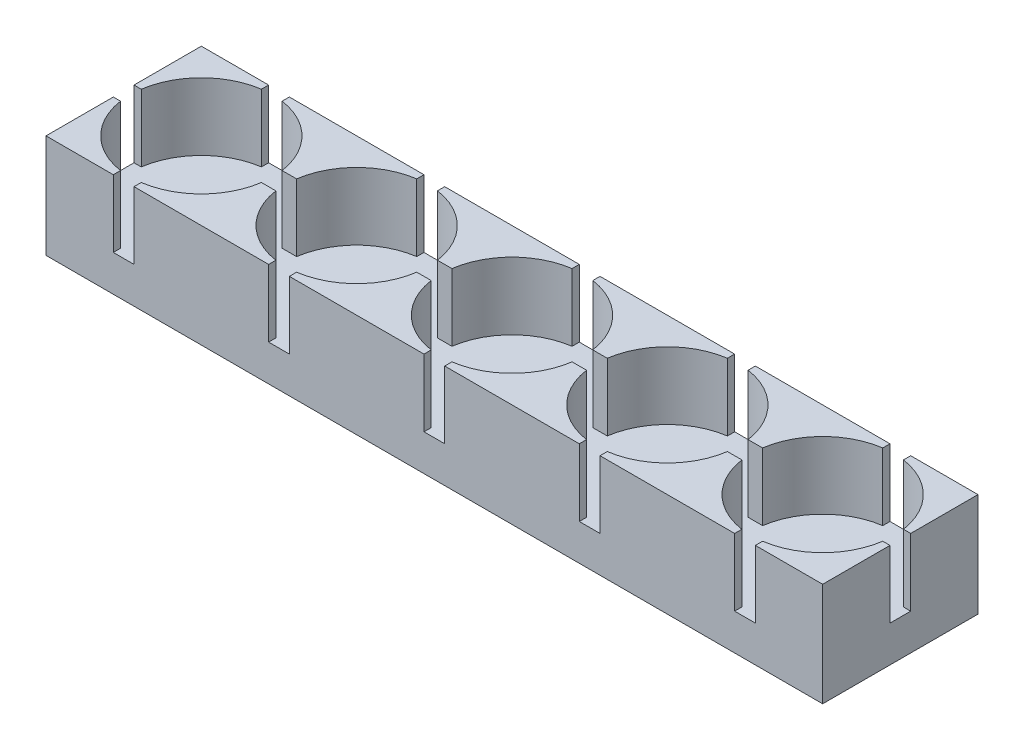
SolidWorks part; units mm, degrees
ref_plane "Front Plane" through (0, 0, 0) normal (0, 0, 1) x (1, 0, 0)
ref_plane "Top Plane" through (0, 0, 0) normal (0, 1, 0) x (1, 0, 0)
ref_plane "Right Plane" through (0, 0, 0) normal (1, 0, 0) x (0, 0, -1)
sketch "Sketch2" plane through (0, 0, 0) normal (0, 1, 0) x (1, 0, 0)
  line L1 (-75, 15) -> (75, 15)
  line L2 (-75, 15) -> (-75, -15)
  line L3 (-75, -15) -> (75, -15)
  line L4 (75, 15) -> (75, -15)
  line L5 (-75, 15) -> (75, -15) construction
  line L6 (-75, -15) -> (75, 15) construction
  point P0 (0, 0)
  dimension "D1" = 150
  dimension "D2" = 30
extrude "Boss-Extrude1" add sketch "Sketch2" along normal blind 20
sketch "Sketch3" plane through (0, 20, 0) normal (0, 1, 0) x (1, 0, 0)
  line L0 (-75, 15) -> (-75, -15) construction
  line L1 (75, 15) -> (-75, 15) construction
  circle A0 centre (-60, 0) radius 13.75
  dimension "D3" = 27.5
  dimension "D1" = 15
  dimension "D2" = 15
extrude "Cut-Extrude1" cut sketch "Sketch3" against normal blind 13
pattern_linear "LPattern1" count 5 spacing 30 along (1, 0, 0) of "Cut-Extrude1"
hole_wizard "CBORE for M4 Hex Socket Head Cap Screw1" positions "Sketch6" profile "Sketch5" counterbore size "M4" standard "DIN" end condition through all
sketch "Sketch6" plane through (0, 7, 0) normal (0, 1, 0) x (-1, 0, 0)
  circle A0 centre (60, 0) radius 13.75 construction
  point P0 (60, 0)
  dimension "D2" = 0
  dimension "D1" = 0
sketch "Sketch5" plane through (-60, 7, 0) normal (1, 0, 0) x (0, 0, 1)
  line L0 (0, 0) -> (0, 7)
  line L1 (0, 7) -> (2.25, 7)
  line L3 (2.25, 7) -> (2.25, 4.4)
  line L4 (2.25, 4.4) -> (4, 4.4)
  line L5 (4, 4.4) -> (4, 0)
  line L7 (4, 0) -> (0, 0)
  line L11 (0, -6.35) -> (0, 107.95) construction
  dimension "Thru Hole Dia." = 4.5
  dimension "Thru Hole Depth" = 7
  dimension "C'Bore Dia." = 8
  dimension "C'Bore Depth" = 4.4
pattern_linear "LPattern2" count 2 spacing 120 along (1, 0, 0) of "CBORE for M4 Hex Socket Head Cap Screw1"
sketch "Sketch7" plane through (0, 20, 0) normal (0, 1, 0) x (1, 0, 0)
  line L1 (-90.5645, -2) -> (90.5645, -2)
  line L2 (-90.5645, -2) -> (-90.5645, 2)
  line L3 (-90.5645, 2) -> (90.5645, 2)
  line L4 (90.5645, -2) -> (90.5645, 2)
  line L5 (-90.5645, -2) -> (90.5645, 2) construction
  line L6 (-90.5645, 2) -> (90.5645, -2) construction
  point P0 (0, 0)
  dimension "D1" = 4
extrude "Cut-Extrude3" cut sketch "Sketch7" against normal blind 13
sketch "Sketch8" plane through (0, 20, 0) normal (0, 1, 0) x (-1, 0, 0)
  line L1 (62, -26.2987) -> (58, -26.2987)
  line L2 (62, -26.2987) -> (62, 23.7013)
  line L3 (62, 23.7013) -> (58, 23.7013)
  line L4 (58, -26.2987) -> (58, 23.7013)
  line L5 (62, -26.2987) -> (58, 23.7013) construction
  line L6 (62, 23.7013) -> (58, -26.2987) construction
  arc A0 (46.3962, -2) -> (73.6038, -2) centre (60, 0) ccw construction
  point P0 (60, -1.2987)
  dimension "D1" = 4
  dimension "D2" = 50
  dimension "D3" = 0
extrude "Cut-Extrude4" cut sketch "Sketch8" against normal blind 13
pattern_linear "LPattern3" count 5 spacing 30 along (1, 0, 0) of "Cut-Extrude4"
